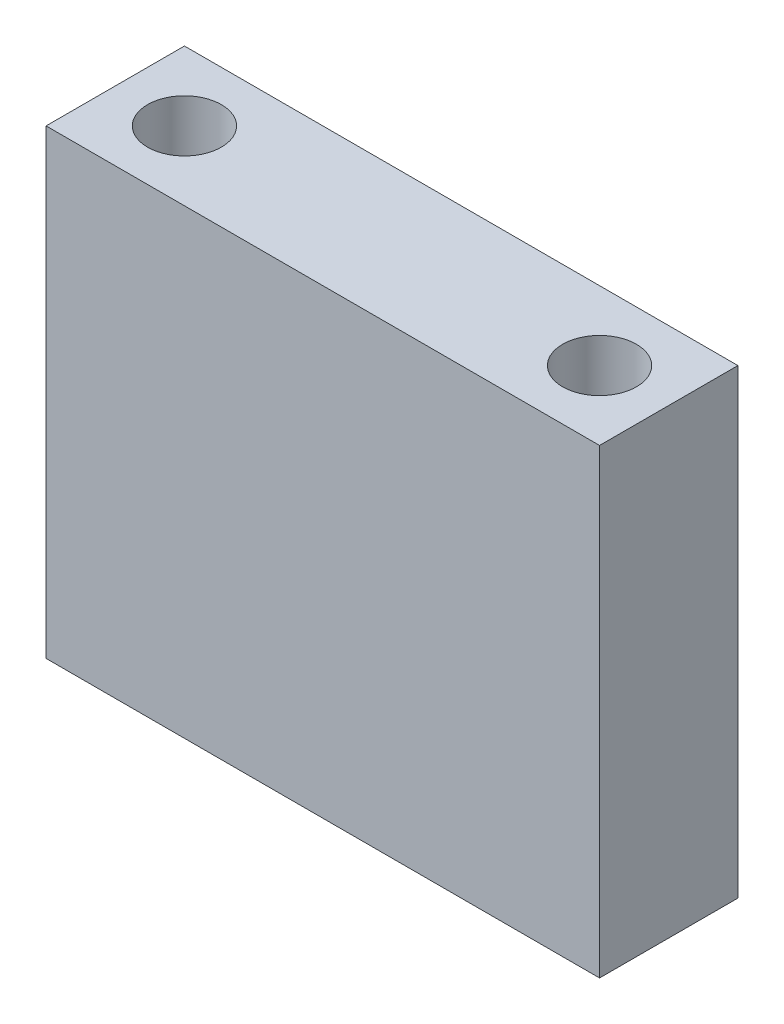
SolidWorks part; units mm, degrees
ref_plane "Front Plane" through (0, 0, 0) normal (0, 0, 1) x (1, 0, 0)
ref_plane "Top Plane" through (0, 0, 0) normal (0, 1, 0) x (1, 0, 0)
ref_plane "Right Plane" through (0, 0, 0) normal (1, 0, 0) x (0, 0, -1)
sketch "Sketch1" plane through (0, 0, 0) normal (0, 0, 1) x (1, 0, 0)
  line L1 (-19.05, 15.875) -> (19.05, 15.875)
  line L2 (-19.05, 15.875) -> (-19.05, -15.875)
  line L3 (-19.05, -15.875) -> (19.05, -15.875)
  line L4 (19.05, 15.875) -> (19.05, -15.875)
  line L5 (-19.05, 15.875) -> (19.05, -15.875) construction
  line L6 (-19.05, -15.875) -> (19.05, 15.875) construction
  point P0 (0, 0)
  dimension "D1" = 31.75
  dimension "D2" = 38.1
extrude "Boss-Extrude1" add sketch "Sketch1" along normal blind 9.525
sketch "Sketch2" plane through (0, 15.875, 0) normal (0, 1, 0) x (1, 0, 0)
  line L0 (-19.05, -9.525) -> (-19.05, 0) construction
  line L1 (19.05, -9.525) -> (19.05, 0) construction
  circle A0 centre (-14.2875, -4.7625) radius 2.54
  circle A1 centre (14.2875, -4.7625) radius 2.54
  point P9 (-19.05, -4.7625)
  dimension "D1" = 5.08
  dimension "D2" = 4.7625
  dimension "D3" = 4.7625
hole_wizard "#6-32 Tapped Hole1" positions "Sketch3" profile "Sketch4" tap size "#6-32" standard "ANSI Inch"
sketch "Sketch3" plane through (0, 15.875, 0) normal (0, 1, 0) x (1, 0, 0)
  point P0 (-14.2875, -4.7625)
  point P3 (14.2875, -4.7625)
sketch "Sketch4" plane through (-14.2875, 15.875, 4.7625) normal (1, 0, 0) x (0, 0, 1)
  line L0 (0, 0) -> (0, 8.4327)
  line L1 (0, 8.4327) -> (1.3525, 7.62)
  line L2 (1.3525, 7.62) -> (1.3525, 0)
  line L5 (1.3525, 0) -> (0, 0)
  line L10 (0, 8.4327) -> (-1.3526, 7.62) construction
  line L11 (0, -6.35) -> (0, 107.95) construction
  dimension "Tap Drill Dia." = 2.7051
  dimension "Tap Drill Depth" = 7.62
  dimension "Drill Angle" = 118
cosmetic thread "Hole Thread1" parameters "D1"=7.0104, "D2"=3.5052
cosmetic thread "Hole Thread2" parameters "D1"=7.0104, "D2"=3.5052
hole_wizard "#6-32 Tapped Hole2" positions "Sketch5" profile "Sketch6" tap size "#6-32" standard "ANSI Inch"
sketch "Sketch5" plane through (0, -15.875, 0) normal (0, -1, 0) x (-1, 0, 0)
  point P0 (-14.2875, -4.7625)
  point P3 (14.2875, -4.7625)
sketch "Sketch6" plane through (14.2875, -15.875, 4.7625) normal (1, 0, 0) x (0, 0, -1)
  line L0 (0, 0) -> (0, 10.2005)
  line L1 (0, 10.2005) -> (1.3525, 9.3878)
  line L2 (1.3525, 9.3878) -> (1.3525, 0)
  line L5 (1.3525, 0) -> (0, 0)
  line L10 (0, 10.2005) -> (-1.3526, 9.3878) construction
  line L11 (0, -6.35) -> (0, 107.95) construction
  dimension "Tap Drill Dia." = 2.7051
  dimension "Tap Drill Depth" = 9.3878
  dimension "Drill Angle" = 118
cosmetic thread "Hole Thread3" parameters "D1"=7.0104, "D2"=3.5052
cosmetic thread "Hole Thread4" parameters "D1"=7.0104, "D2"=3.5052
extrude "Cut-Extrude1" cut sketch "Sketch2" against normal through all
